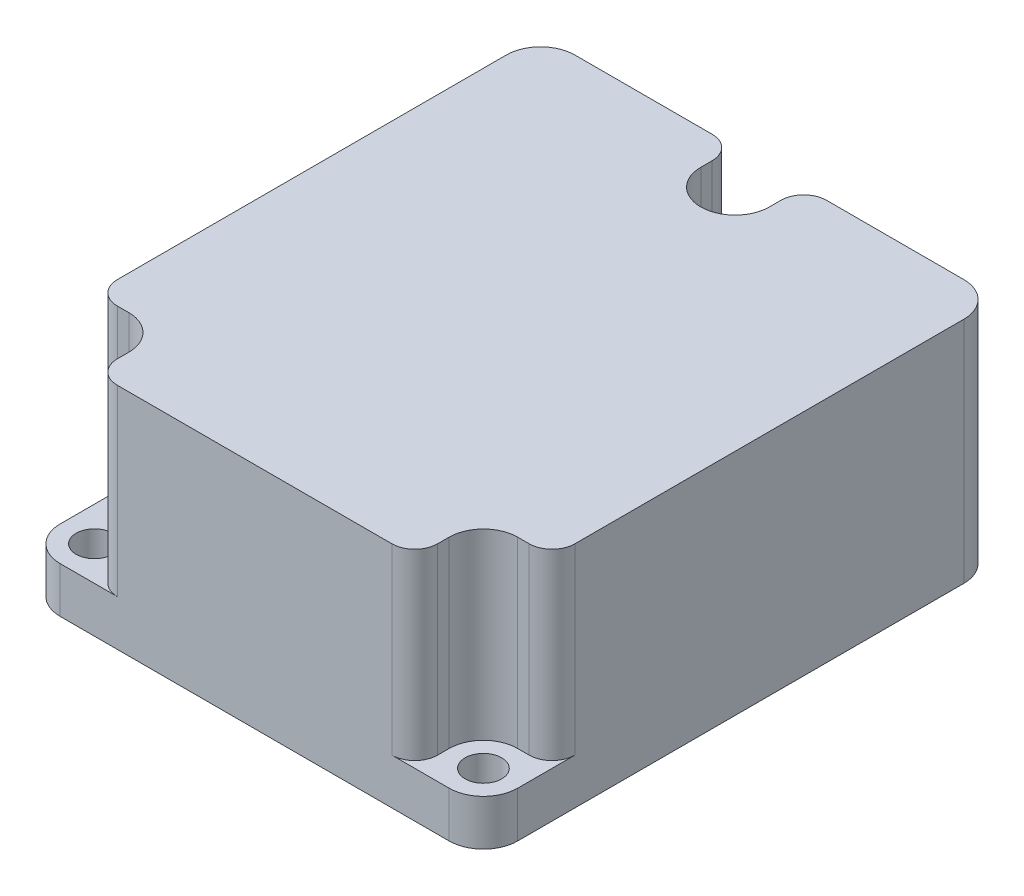
SolidWorks part; units mm, degrees
ref_plane "前视基准面" through (0, 0, 0) normal (0, 0, 1) x (1, 0, 0)
ref_plane "上视基准面" through (0, 0, 0) normal (0, 1, 0) x (1, 0, 0)
ref_plane "右视基准面" through (0, 0, 0) normal (1, 0, 0) x (0, 0, -1)
sketch "草图1" plane through (0, 0, 0) normal (0, 1, 0) x (1, 0, 0)
  line L0 (20, 0) -> (20, -45) construction
  line L1 (3, 0) -> (37, 0)
  line L2 (0, -3) -> (0, -42)
  line L3 (3, -45) -> (37, -45)
  line L4 (40, -3) -> (40, -42)
  line L5 (20, 0) -> (20, -3) construction
  line L6 (20, -45) -> (20, -42) construction
  line L7 (3, -42) -> (37, -42) construction
  circle A0 centre (20, -3) radius 1.6
  circle A1 centre (3, -42) radius 1.6
  circle A2 centre (37, -42) radius 1.6
  arc A3 (0, -42) -> (3, -45) centre (3, -42) ccw
  arc A4 (3, 0) -> (0, -3) centre (3, -3) ccw
  arc A5 (37, 0) -> (40, -3) centre (37, -3) cw
  arc A6 (37, -45) -> (40, -42) centre (37, -42) ccw
  point P13 (20, -42)
  point P19 (0, 0)
  dimension "D1" = 3
extrude "凸台-拉伸1" add sketch "草图1" along normal blind 20
sketch "草图2" plane through (0, 20, 0) normal (0, 1, 0) x (1, 0, 0)
  line L0 (17, -3) -> (17, 0)
  line L1 (23, -3) -> (23, 0)
  line L2 (6, -42) -> (6, -45)
  line L3 (3, -39) -> (0, -39)
  line L4 (3, -45) -> (37, -45)
  line L5 (40, -42) -> (40, -3)
  line L6 (37, 0) -> (3, 0)
  line L7 (0, -3) -> (0, -42)
  line L8 (3, -45) -> (37, -45)
  line L9 (40, -42) -> (40, -3)
  line L10 (37, 0) -> (3, 0)
  line L11 (0, -3) -> (0, -42)
  line L12 (34, -42) -> (34, -45)
  line L13 (37, -39) -> (40, -39)
  arc A0 (37, -45) -> (40, -42) centre (37, -42) ccw
  arc A1 (0, -42) -> (3, -45) centre (3, -42) ccw
  arc A2 (17, -3) -> (23, -3) centre (20, -3) ccw
  arc A3 (6, -42) -> (3, -39) centre (3, -42) ccw
  arc A4 (0, -42) -> (3, -45) centre (3, -42) ccw
  arc A5 (37, -45) -> (40, -42) centre (37, -42) ccw
  arc A6 (40, -3) -> (37, 0) centre (37, -3) ccw
  arc A7 (3, 0) -> (0, -3) centre (3, -3) ccw
  arc A8 (0, -42) -> (3, -45) centre (3, -42) ccw
  arc A9 (37, -45) -> (40, -42) centre (37, -42) ccw
  arc A10 (40, -3) -> (37, 0) centre (37, -3) ccw
  arc A11 (3, 0) -> (0, -3) centre (3, -3) ccw
  arc A12 (37, -39) -> (34, -42) centre (37, -42) ccw
  circle M10 centre (3, -42) radius 1.6
  arc M11 (0, -42) -> (3, -45) centre (3, -42) ccw
  line M12 (3, -45) -> (37, -45)
  arc M13 (37, -45) -> (40, -42) centre (37, -42) ccw
  line M14 (40, -42) -> (40, -3)
  line M16 (37, 0) -> (3, 0)
  line M18 (0, -3) -> (0, -42)
  circle M19 centre (20, -3) radius 1.6
  circle M20 centre (37, -42) radius 1.6
  dimension "D1" = 0
extrude "切除-拉伸1" cut sketch "草图2" against normal blind 16 contours L13 A12 L12 L8 M13 M14 M20 | L2 A3 L3 M18 M11 M12 M10 | L0 A2 L1 M16 M19
fillet "圆角1" radius 2 6 edges at (34, 12, 45) (40, 12, 39) (17, 12, 0) (23, 12, 0) (6, 12, 45) (0, 12, 39)
sketch "草图3" plane through (0, 0, 45) normal (0, 0, 1) x (1, 0, 0)
  line L0 (20, 20) -> (20, 0) construction
  line L1 (8, 20) -> (32, 20) construction
  line L2 (3, 0) -> (37, 0) construction
  circle A0 centre (20, 10) radius 7
extrude "凸台-拉伸2" add sketch "草图3" along normal blind 50
sketch "草图4" plane through (0, 0, 95) normal (0, 0, 1) x (1, 0, 0)
  circle A1 centre (20, 10) radius 7
  circle A2 centre (20, 10) radius 7
  dimension "D1" = 0
extrude "切除-拉伸2" cut sketch "草图4" against normal blind 50
ref_plane "基准面1" through (0, 0, 22.5) normal (0, 0, 1) x (1, 0, 0)
sketch "草图5" plane through (0, 0, 45) normal (0, 0, 1) x (1, 0, 0)
  point P0 (0, 0)
  point P1 (0, 0)
